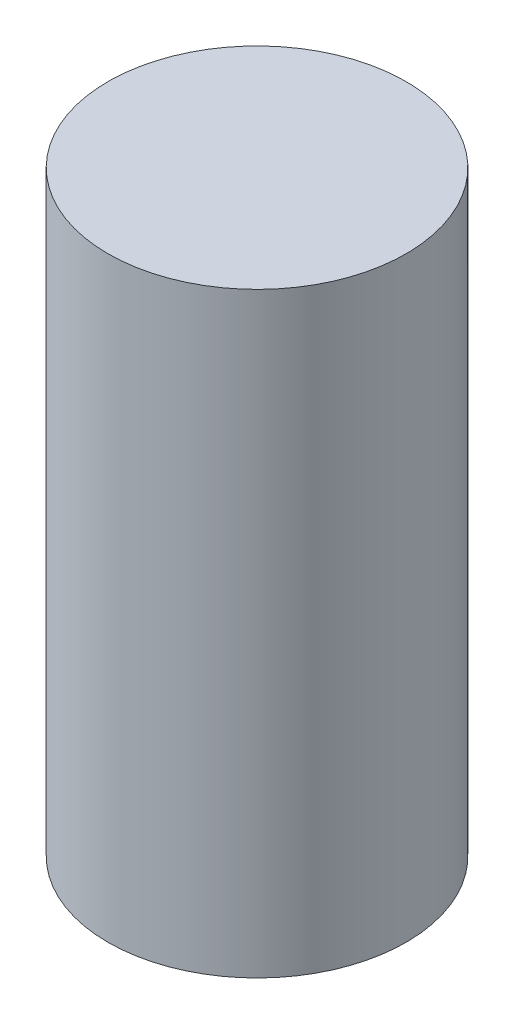
SolidWorks part; units mm, degrees
ref_plane "前视基准面" through (0, 0, 0) normal (0, 0, 1) x (1, 0, 0)
ref_plane "上视基准面" through (0, 0, 0) normal (0, 1, 0) x (1, 0, 0)
ref_plane "右视基准面" through (0, 0, 0) normal (1, 0, 0) x (0, 0, -1)
other "Configuration Table"
sketch "草图1" plane through (0, 0, 0) normal (0, 1, 0) x (1, 0, 0)
  circle A0 centre (0, 0) radius 10
extrude "凸台-拉伸1" add sketch "草图1" along normal blind 40
